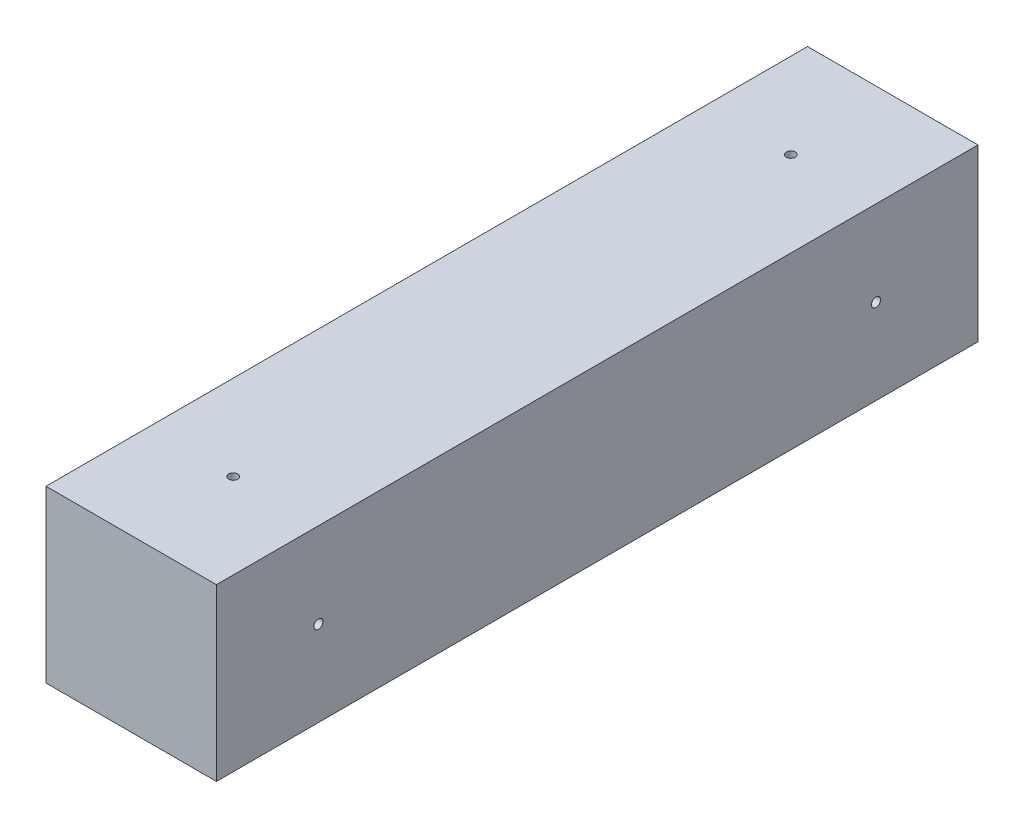
SolidWorks part; units mm, degrees
material "Pin"
ref_plane "Plan de face" through (0, 0, 0) normal (0, 0, 1) x (1, 0, 0)
ref_plane "Plan de dessus" through (0, 0, 0) normal (0, 1, 0) x (1, 0, 0)
ref_plane "Plan de droite" through (0, 0, 0) normal (1, 0, 0) x (0, 0, -1)
sketch "Esquisse1" plane through (0, 0, 0) normal (0, 0, 1) x (1, 0, 0)
  line L0 (-25.4, 25.4) -> (25.4, -25.4) construction
  line L1 (-25.4, 25.4) -> (25.4, 25.4)
  line L2 (-25.4, 25.4) -> (-25.4, -25.4)
  line L3 (-25.4, -25.4) -> (25.4, -25.4)
  line L4 (25.4, 25.4) -> (25.4, -25.4)
  line L5 (-25.4, -25.4) -> (25.4, 25.4) construction
  point P4 (0, 0)
  dimension "D1" = 50.8
extrude "Boss.-Extru.1" add sketch "Esquisse1" along normal mid plane 227
hole_wizard "Trou pour taraudage pour trou taraudé #6-321" positions "Esquisse2" profile "Esquisse4" hole size "#6-32" standard "Ansi Inch" end condition through all
sketch "Esquisse2" plane through (25.4, 0, 0) normal (1, 0, 0) x (0, 0, -1)
  line L0 (-113.5, -25.4) -> (-113.5, 25.4) construction
  line L1 (113.5, -25.4) -> (113.5, 25.4) construction
  point P0 (-83.1, 0)
  point P2 (83.1, 0)
  point P9 (113.5, 0)
  point P11 (-113.5, 0)
  dimension "D1" = 30.4
  dimension "D2" = 30.4
sketch "Esquisse4" plane through (25.4, 0, 83.1) normal (0, 1, 0) x (0, 0, -1)
  line L0 (0, 0) -> (0, 50.8)
  line L1 (0, 50.8) -> (1.3525, 50.8)
  line L2 (1.3525, 50.8) -> (1.3525, 0)
  line L5 (1.3525, 0) -> (0, 0)
  line L11 (0, -6.35) -> (0, 107.95) construction
  dimension "Diamètre du perçage jusqu'au prochain" = 2.7051
  dimension "Profondeur du perçage jusqu'au prochain" = 50.8
hole_wizard "Trou pour taraudage pour trou taraudé #6-322" positions "Esquisse5" profile "Esquisse6" hole size "#6-32" standard "Ansi Inch"
sketch "Esquisse5" plane through (0, 25.4, 0) normal (0, 1, 0) x (1, 0, 0)
  line L0 (25.4, -113.5) -> (-25.4, -113.5) construction
  line L1 (25.4, 113.5) -> (-25.4, 113.5) construction
  point P0 (0, -65.2)
  point P2 (0, 65.2)
  point P10 (0, 113.5)
  point P12 (0, -113.5)
  dimension "D1" = 48.3
  dimension "D2" = 48.3
sketch "Esquisse6" plane through (0, 25.4, 65.2) normal (1, 0, 0) x (0, 0, 1)
  line L0 (0, 0) -> (0, 50.8)
  line L1 (0, 50.8) -> (1.3525, 50.8)
  line L2 (1.3525, 50.8) -> (1.3525, 0)
  line L5 (1.3525, 0) -> (0, 0)
  line L11 (0, -6.35) -> (0, 107.95) construction
  dimension "Diamètre du perçage jusqu'au prochain" = 2.7051
  dimension "Profondeur du perçage jusqu'au prochain" = 50.8
hole_wizard "Trou pour taraudage pour trou taraudé #6-323" positions "Esquisse7" profile "Esquisse8" hole size "#6-32" standard "Ansi Inch"
sketch "Esquisse7" plane through (0, 25.4, 0) normal (0, 1, 0) x (1, 0, 0)
  point P4 (0, 0)
sketch "Esquisse8" plane through (0, 25.4, 0) normal (1, 0, 0) x (0, 0, 1)
  line L0 (0, 0) -> (0, 50.8)
  line L1 (0, 50.8) -> (1.3525, 50.8)
  line L2 (1.3525, 50.8) -> (1.3525, 0)
  line L5 (1.3525, 0) -> (0, 0)
  line L11 (0, -6.35) -> (0, 107.95) construction
  dimension "Diamètre du perçage jusqu'au prochain" = 2.7051
  dimension "Profondeur du perçage jusqu'au prochain" = 50.8
hole_wizard "Trou pour taraudage pour trou taraudé #6-324" positions "Esquisse11" profile "Esquisse10" hole size "#6-32" standard "Ansi Inch" end condition through all
sketch "Esquisse11" plane through (0, 25.4, 0) normal (0, 1, 0) x (1, 0, 0)
  line L0 (25.4, -113.5) -> (-25.4, -113.5) construction
  line L1 (25.4, 113.5) -> (-25.4, 113.5) construction
  point P0 (0, -83.1)
  point P2 (0, 83.1)
  point P5 (0, 0)
  point P6 (0, 0)
  dimension "D1" = 30.4
  dimension "D2" = 30.4
sketch "Esquisse10" plane through (0, 25.4, 83.1) normal (1, 0, 0) x (0, 0, 1)
  line L0 (0, 0) -> (0, 50.8)
  line L1 (0, 50.8) -> (1.3525, 50.8)
  line L2 (1.3525, 50.8) -> (1.3525, 0)
  line L5 (1.3525, 0) -> (0, 0)
  line L11 (0, -6.35) -> (0, 107.95) construction
  dimension "Diamètre du perçage jusqu'au prochain" = 2.7051
  dimension "Profondeur du perçage jusqu'au prochain" = 50.8
